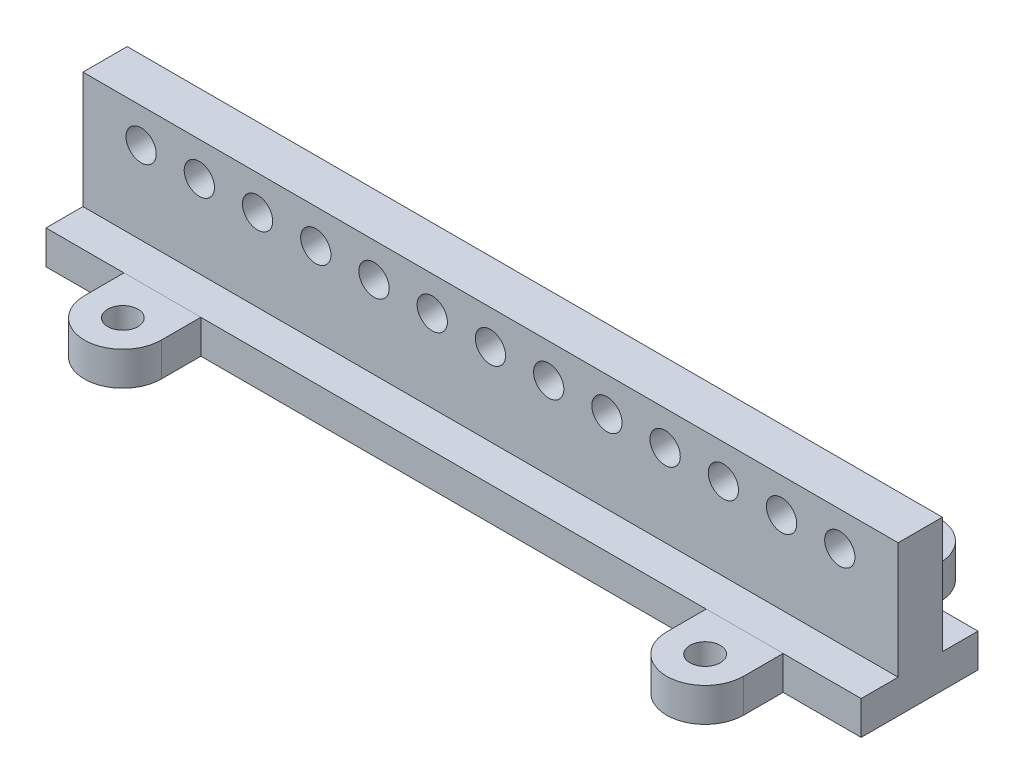
SolidWorks part; units mm, degrees
ref_plane "Front Plane" through (0, 0, 0) normal (0, 0, 1) x (1, 0, 0)
ref_plane "Top Plane" through (0, 0, 0) normal (0, 1, 0) x (1, 0, 0)
ref_plane "Right Plane" through (0, 0, 0) normal (1, 0, 0) x (0, 0, -1)
sketch "Sketch1" plane through (0, 0, 0) normal (0, 0, 1) x (1, 0, 0)
  line L1 (0, 0) -> (-88.9, 0)
  line L2 (0, 0) -> (0, 25.4)
  line L3 (0, 25.4) -> (-88.9, 25.4)
  line L4 (-88.9, 0) -> (-88.9, 25.4)
  dimension "D1" = 25.4
  dimension "D2" = 88.9
extrude "Boss-Extrude1" add sketch "Sketch1" along normal blind 4.826
sketch "Sketch3" plane through (0, 0, 4.826) normal (0, 0, 1) x (1, 0, 0)
  line L0 (-88.9, 0) -> (-88.9, 12.7)
  line L1 (-88.9, 25.4) -> (-88.9, 0) construction
  line L2 (-88.9, 12.7) -> (0, 12.7)
  line L3 (0, 0) -> (0, 25.4) construction
  line L5 (-88.9, 0) -> (0, 0)
  line L6 (-88.9, 0) -> (-88.9, 12.7)
  line L7 (-88.9, 12.7) -> (0, 12.7)
  line L8 (0, 0) -> (0, 12.7)
  line M14 (0, 0) -> (0, 25.4)
  line M16 (-88.9, 25.4) -> (-88.9, 0)
  line M17 (-88.9, 0) -> (0, 0)
extrude "Cut-Extrude2" cut sketch "Sketch3" against normal through all contours L2 M16 M17 M14
ref_plane "Plane1" through (-88.9, 0, 0) normal (-1, 0, 0) x (0, 0, 1)
sketch "Sketch6" plane through (-88.9, 0, 0) normal (-1, 0, 0) x (0, 0, 1)
  line L0 (2.413, 12.7) -> (8.8553, 12.7)
  line L1 (0, 12.7) -> (4.826, 12.7) construction
  line L2 (2.413, 12.7) -> (-3.8853, 12.7)
  line L3 (-3.8853, 12.7) -> (-3.8853, 19.05)
  line L4 (-3.8853, 19.05) -> (8.8553, 19.05)
  line L5 (8.8553, 19.05) -> (8.8553, 12.7)
  dimension "D1" = 6.35
extrude "Boss-Extrude2" add sketch "Sketch6" against normal blind 88.9
sketch "Sketch7" plane through (0, 0, 8.8553) normal (0, 0, 1) x (1, 0, 0)
  line L0 (-88.9, 10.3018) -> (-88.9, -10.3018) construction
  line L1 (0, 12.7) -> (-88.9, 12.7)
  line L2 (0, 12.7) -> (0, 15.3769)
  line L3 (0, 15.3769) -> (-88.9, 15.3769)
  line L4 (-88.9, 12.7) -> (-88.9, 15.3769)
extrude "Cut-Extrude3" cut sketch "Sketch7" against normal through all
sketch "Sketch8" plane through (0, 0, 4.826) normal (0, 0, 1) x (1, 0, 0)
  line L0 (-88.9, 25.4) -> (-88.9, 21.6668) construction
  line L1 (-88.9, 10.3018) -> (-88.9, -10.3018) construction
  line L2 (0, 25.4) -> (-88.9, 25.4) construction
  line L3 (-88.9, 21.6668) -> (0, 21.6668) construction
  line L4 (0, 19.05) -> (0, 25.4) construction
sketch "Sketch9" plane through (-88.9, 0, 0) normal (-1, 0, 0) x (0, 0, 1)
  line L1 (4.826, 25.4) -> (4.826, 31.75)
  line L2 (0, 25.4) -> (0, 31.75)
  line L3 (0, 31.75) -> (4.826, 31.75)
  line L4 (0, 25.4) -> (4.826, 25.4)
  dimension "D1" = 6.35
extrude "Boss-Extrude3" add sketch "Sketch9" against normal blind 88.9
sketch "Sketch11" plane through (0, 0, 4.826) normal (0, 0, 1) x (1, 0, 0)
  line L0 (-88.9, 31.75) -> (-88.9, 28.0126) construction
  line L1 (-88.9, 31.75) -> (-88.9, 19.05) construction
  line L2 (-88.9, 28.0126) -> (0, 28.0126) construction
  line L3 (0, 19.05) -> (0, 31.75) construction
  line L4 (-88.9, 28.0126) -> (-82.5572, 28.0126) construction
  circle A0 centre (-82.5572, 28.0126) radius 1.651
  circle A1 centre (-76.2072, 28.0126) radius 1.651
  circle A2 centre (-69.8572, 28.0126) radius 1.651
  circle A3 centre (-63.5072, 28.0126) radius 1.651
  circle A4 centre (-57.1572, 28.0126) radius 1.651
  circle A5 centre (-50.8072, 28.0126) radius 1.651
  circle A6 centre (-44.4572, 28.0126) radius 1.651
  circle A7 centre (-38.1072, 28.0126) radius 1.651
  circle A8 centre (-31.7572, 28.0126) radius 1.651
  circle A9 centre (-25.4072, 28.0126) radius 1.651
  circle A10 centre (-19.0572, 28.0126) radius 1.651
  circle A11 centre (-12.7072, 28.0126) radius 1.651
  circle A12 centre (-6.3572, 28.0126) radius 1.651
  dimension "D1" = 3.302
  dimension "D2" = 13
extrude "Cut-Extrude4" cut sketch "Sketch11" against normal through all
ref_plane "Plane3" through (0, 15.3769, 0) normal (0, -1, 0) x (-1, 0, 0)
sketch "Sketch13" plane through (0, 15.3769, 0) normal (0, -1, 0) x (-1, 0, 0)
  line L0 (88.9, -8.8553) -> (80.391, -8.8553) construction
  line L1 (0, -8.8553) -> (88.9, -8.8553) construction
  line L4 (80.391, -8.8553) -> (80.391, -13.1733)
  line L6 (72.009, -13.1733) -> (72.009, -8.8553)
  line L7 (80.391, -8.8553) -> (72.009, -8.8553)
  line L9 (72.009, 3.8853) -> (72.009, 8.2033)
  line L10 (80.391, 8.2033) -> (80.391, 3.8853)
  line L11 (72.009, 3.8853) -> (80.391, 3.8853)
  line L12 (76.2, -13.1733) -> (76.2, 17.7034) construction
  line L13 (0, 3.8853) -> (88.9, 3.8853) construction
  arc A0 (72.009, -13.1733) -> (80.391, -13.1733) centre (76.2, -13.1733) ccw
  circle A1 centre (76.2, -13.1733) radius 1.651
  arc A2 (80.391, 8.2033) -> (72.009, 8.2033) centre (76.2, 8.2033) ccw
  circle A3 centre (76.2, 8.2033) radius 1.651
  dimension "D1" = 3.302
  dimension "D2" = 4.318
extrude "Boss-Extrude4" add sketch "Sketch13" against normal blind 3.683
ref_plane "Plane4" through (0, 0, 2.4647) normal (0, 0, -1) x (-1, 0, 0)
ref_plane "Plane5" through (-44.45, 0, 0) normal (1, 0, 0) x (0, 0, -1)
mirror "Mirror2" about plane through (-44.45, 0, 0) normal (1, 0, 0) of "Boss-Extrude4"
ref_plane "Plane6" through (0, 0, -3.8853) normal (0, 0, -1) x (-1, 0, 0)
